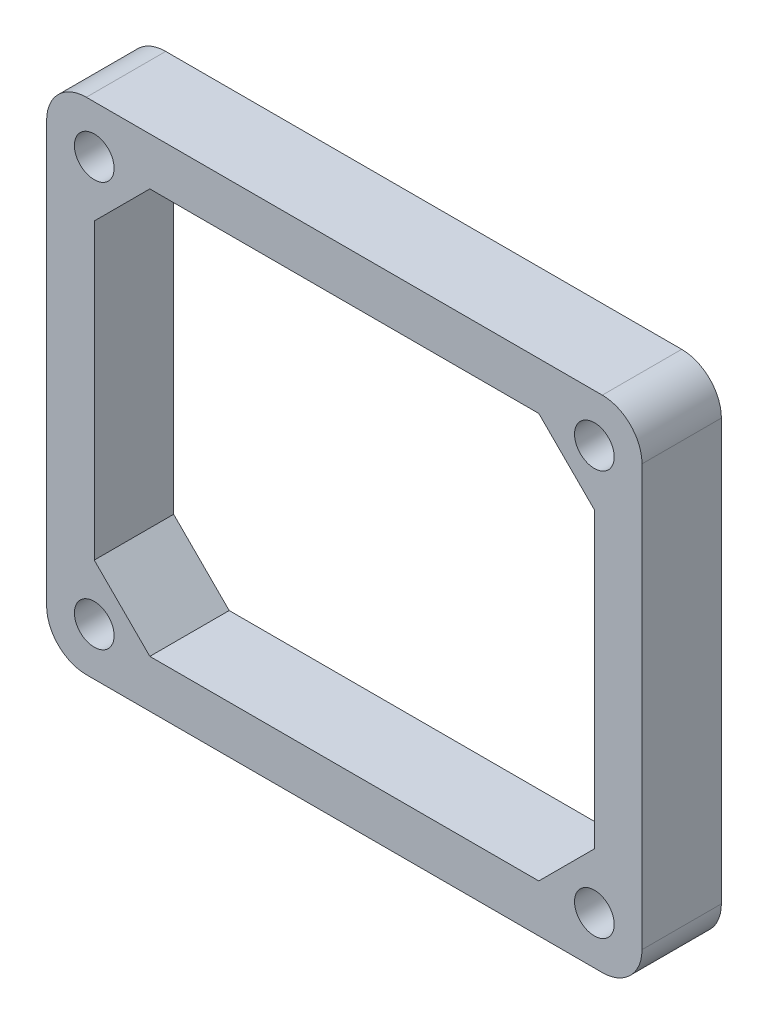
SolidWorks part; units mm, degrees
ref_plane "Front Plane" through (0, 0, 0) normal (0, 0, 1) x (1, 0, 0)
ref_plane "Top Plane" through (0, 0, 0) normal (0, 1, 0) x (1, 0, 0)
ref_plane "Right Plane" through (0, 0, 0) normal (1, 0, 0) x (0, 0, -1)
sketch "Sketch1" plane through (0, 0, 0) normal (0, 0, 1) x (1, 0, 0)
  line L0 (-33.3185, 4.103) -> (-26.3185, 11.103)
  line L1 (-39.3185, 17.103) -> (35.6815, 17.103)
  line L2 (-39.3185, 17.103) -> (-39.3185, -45.897)
  line L3 (-39.3185, -45.897) -> (35.6815, -45.897)
  line L4 (35.6815, 17.103) -> (35.6815, -45.897)
  line L5 (-26.3185, 11.103) -> (22.6815, 11.103)
  line L6 (-33.3185, 4.103) -> (-33.3185, -32.897)
  line L7 (-26.3185, -39.897) -> (22.6815, -39.897)
  line L8 (29.6815, 4.103) -> (29.6815, -32.897)
  line L9 (22.6815, 11.103) -> (29.6815, 4.103)
  line L10 (29.6815, -32.897) -> (22.6815, -39.897)
  line L11 (-33.3185, -32.897) -> (-26.3185, -39.897)
  circle A0 centre (-33.3185, 11.103) radius 2.5
  circle A1 centre (29.6815, 11.103) radius 2.5
  circle A2 centre (29.6815, -39.897) radius 2.5
  circle A3 centre (-33.3185, -39.897) radius 2.5
  point P4 (-33.3185, 11.103)
  point P5 (29.6815, -39.897)
  point P6 (-33.3185, -39.897)
  point P7 (29.6815, 11.103)
  dimension "D7" = 5
  dimension "D8" = 5
  dimension "D13" = 5
  dimension "D14" = 5
  dimension "D1" = 75
  dimension "D2" = 63
  dimension "D3" = 6
  dimension "D4" = 6
  dimension "D5" = 6
  dimension "D6" = 6
extrude "Boss-Extrude1" add sketch "Sketch1" along normal blind 10
fillet "Fillet1" radius 5 4 edges at (-39.3185, -45.897, 5) (35.6815, -45.897, 5) (35.6815, 17.103, 5) (-39.3185, 17.103, 5)
